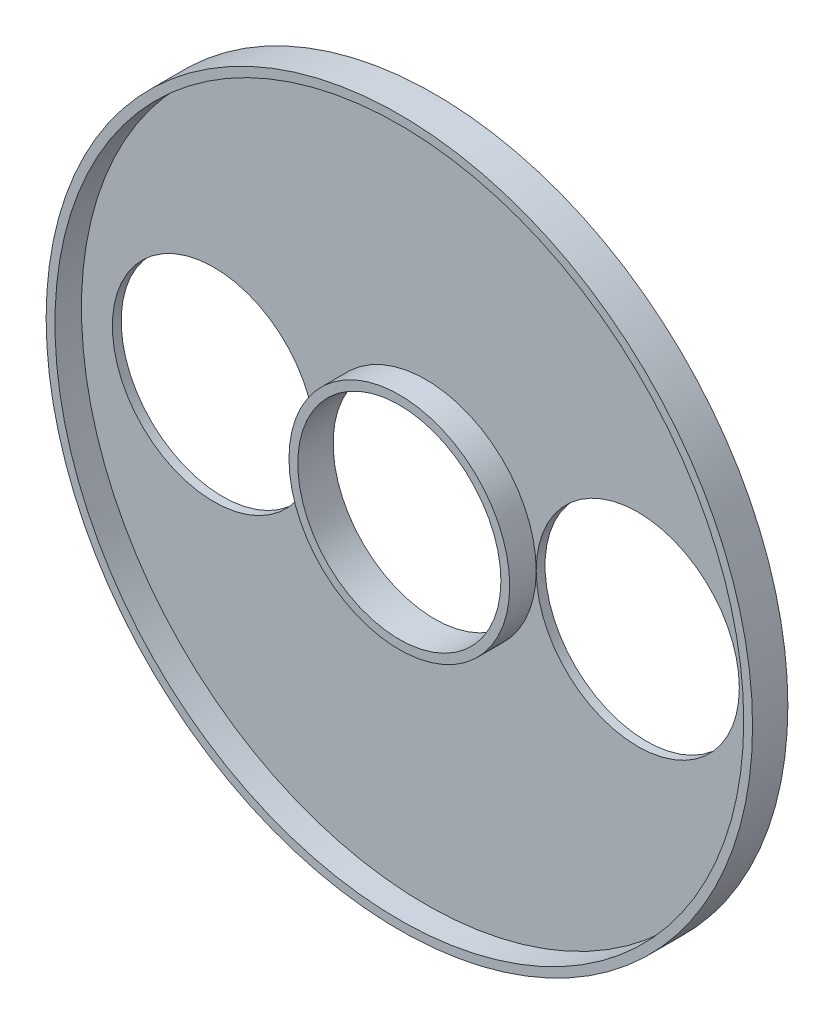
SolidWorks part; units mm, degrees
ref_plane "Спереди" through (0, 0, 0) normal (0, 0, 1) x (1, 0, 0)
ref_plane "Сверху" through (0, 0, 0) normal (0, 1, 0) x (1, 0, 0)
ref_plane "Справа" through (0, 0, 0) normal (1, 0, 0) x (0, 0, -1)
sketch "Эскиз1" plane through (0, 0, 0) normal (0, 0, 1) x (1, 0, 0)
  circle A0 centre (0, 0) radius 80
  circle A1 centre (0, 0) radius 23
extrude "Plenum_backplate" add sketch "Эскиз1" along normal blind 2 from offset 52
sketch "Эскиз2" plane through (0, 0, 0) normal (0, 0, 1) x (1, 0, 0)
  circle A0 centre (0, 0) radius 80
  circle A1 centre (0, 0) radius 78
extrude "Plenum_outer_wall" add sketch "Эскиз2" along normal blind 8 from offset 52
sketch "Эскиз3" plane through (0, 0, 0) normal (0, 0, 1) x (1, 0, 0)
  circle A0 centre (0, 0) radius 25
  circle A1 centre (0, 0) radius 23
extrude "Plenum_inner_wall" add sketch "Эскиз3" along normal blind 8 from offset 52
sketch "Эскиз4" plane through (0, 0, 0) normal (0, 0, 1) x (1, 0, 0)
  circle A0 centre (-48, 0) radius 23
  circle A1 centre (48, 0) radius 23
extrude "Through_holes" cut sketch "Эскиз4" against normal mid plane 200
